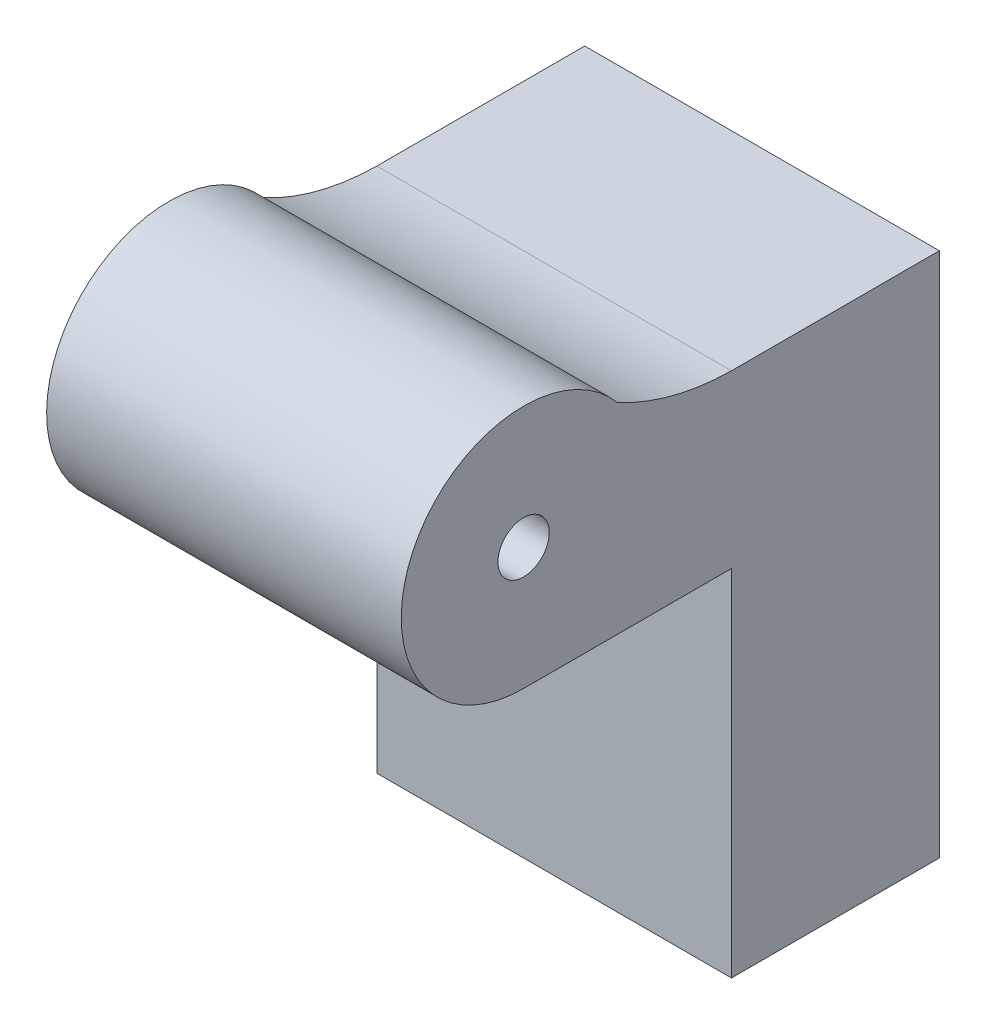
SolidWorks part; units mm, degrees
ref_plane "Alzado" through (0, 0, 0) normal (0, 0, 1) x (1, 0, 0)
ref_plane "Planta" through (0, 0, 0) normal (0, 1, 0) x (1, 0, 0)
ref_plane "Vista lateral" through (0, 0, 0) normal (1, 0, 0) x (0, 0, -1)
sketch "Croquis1" plane through (0, 0, 0) normal (0, 1, 0) x (1, 0, 0)
  line L1 (0, 0) -> (29, 0)
  line L2 (0, 0) -> (0, -17)
  line L3 (0, -17) -> (29, -17)
  line L4 (29, 0) -> (29, -17)
  dimension "D1" = 29
  dimension "D2" = 17
extrude "Saliente-Extruir1" add sketch "Croquis1" along normal blind 43
sketch "Croquis2" plane through (29, 0, 0) normal (1, 0, 0) x (0, 0, -1)
  line L0 (-17, 43) -> (0, 43) construction
  line L2 (-17, 43) -> (-17, 0) construction
  circle A0 centre (-34, 39) radius 10
  dimension "D1" = 20
  dimension "D2" = 4
  dimension "D3" = 17
extrude "Saliente-Extruir2" add sketch "Croquis2" against normal up to surface (29 mm away) separate body up to face at (0, 21.5, 8.5)
sketch "Croquis3" plane through (29, 0, 0) normal (1, 0, 0) x (0, 0, -1)
  circle A0 centre (-34, 39) radius 2.1
  dimension "D1" = 4.2
extrude "Cortar-Extruir1" cut sketch "Croquis3" against normal up to surface (29 mm away) up to face at (0, 39, 24)
sketch "Croquis4" plane through (29, 0, 0) normal (1, 0, 0) x (0, 0, -1)
  line L1 (-17, 29) -> (-17, 43)
  line L3 (-34, 29) -> (-17, 29)
  circle A1 centre (-34, 39) radius 10 construction
  arc A2 (-17, 43) -> (-26.3345, 45.4218) centre (-16.7628, 63.1143) cw
  arc A3 (-34, 29) -> (-26.3345, 45.4218) centre (-34, 39) ccw
extrude "Saliente-Extruir3" add sketch "Croquis4" against normal up to surface (29 mm away) up to face at (0, 39, 31.9)
